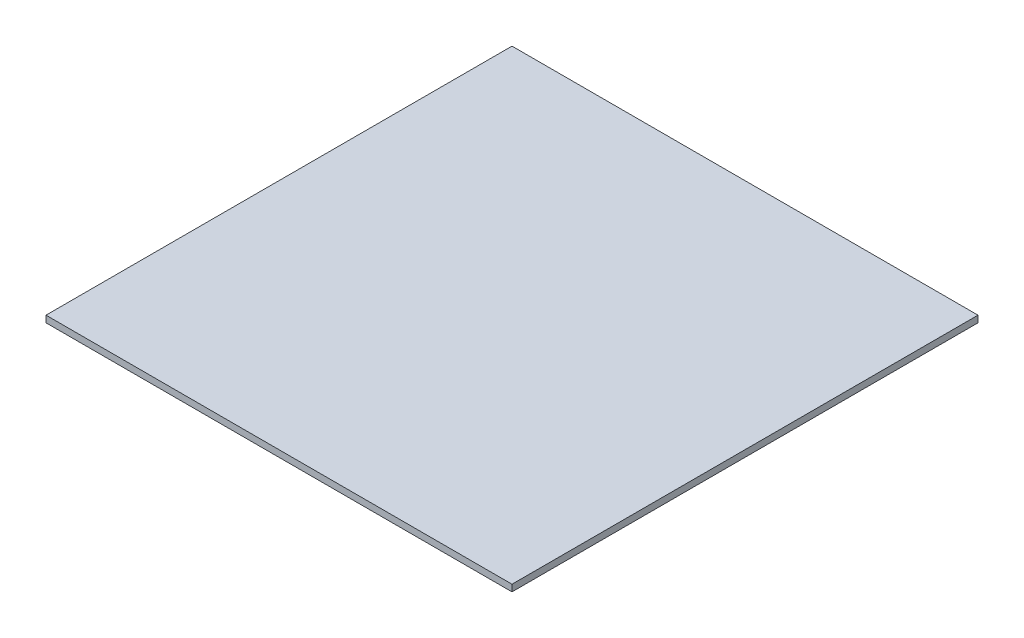
SolidWorks part; units mm, degrees
ref_plane "Front Plane" through (0, 0, 0) normal (0, 0, 1) x (1, 0, 0)
ref_plane "Top Plane" through (0, 0, 0) normal (0, 1, 0) x (1, 0, 0)
ref_plane "Right Plane" through (0, 0, 0) normal (1, 0, 0) x (0, 0, -1)
sketch "Sketch1" plane through (0, 0, 0) normal (0, 1, 0) x (1, 0, 0)
  line L1 (-350, -350) -> (350, -350)
  line L2 (-350, -350) -> (-350, 350)
  line L3 (-350, 350) -> (350, 350)
  line L4 (350, -350) -> (350, 350)
  line L5 (-350, -350) -> (350, 350) construction
  line L6 (-350, 350) -> (350, -350) construction
  point P0 (0, 0)
  dimension "D1" = 700
  dimension "D2" = 700
extrude "Boss-Extrude1" add sketch "Sketch1" along normal blind 10
